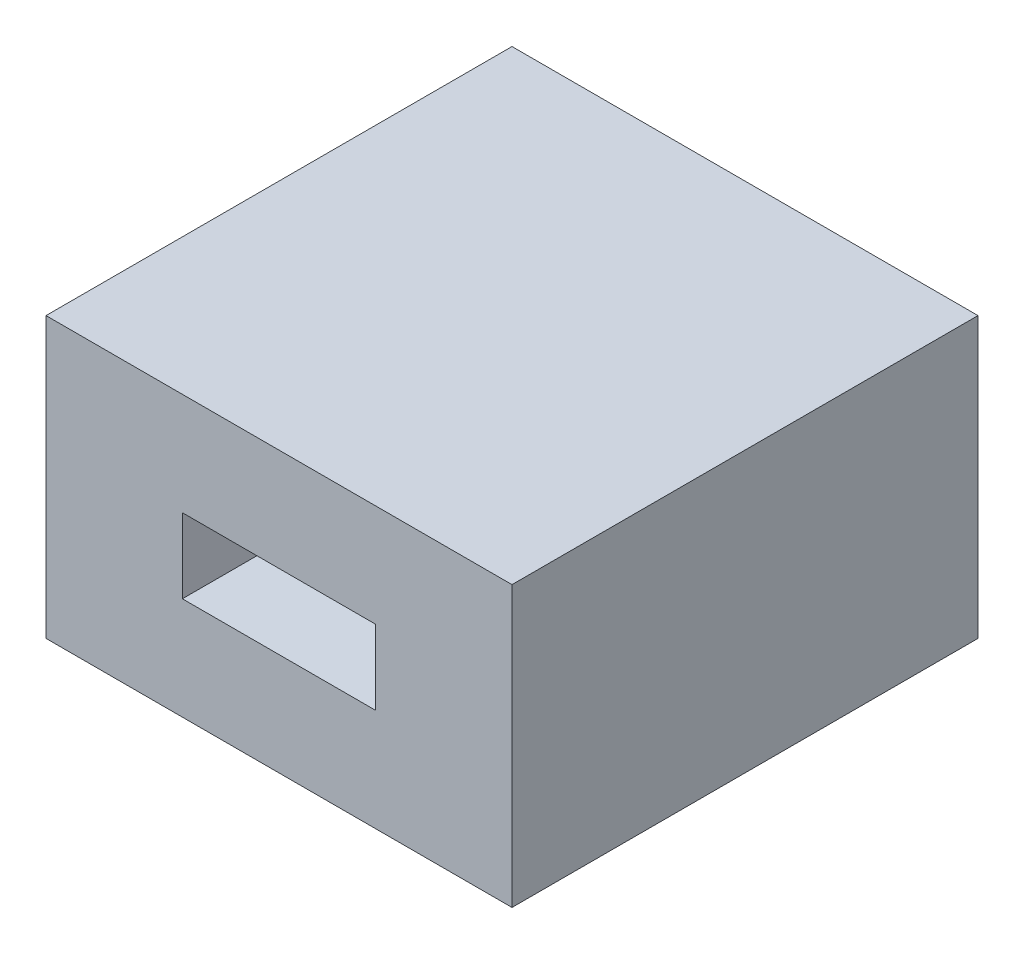
SolidWorks part; units mm, degrees
ref_plane "Front Plane" through (0, 0, 0) normal (0, 0, 1) x (1, 0, 0)
ref_plane "Top Plane" through (0, 0, 0) normal (0, 1, 0) x (1, 0, 0)
ref_plane "Right Plane" through (0, 0, 0) normal (1, 0, 0) x (0, 0, -1)
sketch "Sketch1" plane through (0, 0, 0) normal (0, 1, 0) x (1, 0, 0)
  line L1 (-12.5, 12.5) -> (12.5, 12.5)
  line L2 (-12.5, 12.5) -> (-12.5, -12.5)
  line L3 (-12.5, -12.5) -> (12.5, -12.5)
  line L4 (12.5, 12.5) -> (12.5, -12.5)
  line L5 (-12.5, 12.5) -> (12.5, -12.5) construction
  line L6 (-12.5, -12.5) -> (12.5, 12.5) construction
  point P0 (0, 0)
  dimension "D1" = 25
  dimension "D2" = 25
extrude "Boss-Extrude1" add sketch "Sketch1" along normal blind 15
sketch "Sketch2" plane through (0, 0, 12.5) normal (0, 0, 1) x (1, 0, 0)
  line L0 (0, 15) -> (0, 0) construction
  line L1 (-12.5, 15) -> (12.5, 15) construction
  line L2 (13.75, 0) -> (-13.75, 0) construction
  line L3 (-5.1832, 9.5) -> (5.1832, 9.5)
  line L4 (-5.1832, 9.5) -> (-5.1832, 5.5)
  line L5 (-5.1832, 5.5) -> (5.1832, 5.5)
  line L6 (5.1832, 9.5) -> (5.1832, 5.5)
  line L7 (-5.1832, 9.5) -> (5.1832, 5.5) construction
  line L8 (-5.1832, 5.5) -> (5.1832, 9.5) construction
  point P5 (0, 7.5)
  dimension "D1" = 5.5
  dimension "D2" = 4
  dimension "D3" = 5.5
extrude "Cut-Extrude1" cut sketch "Sketch2" against normal blind 24 draft 3.5
equation "\"1.5c\"=10"
